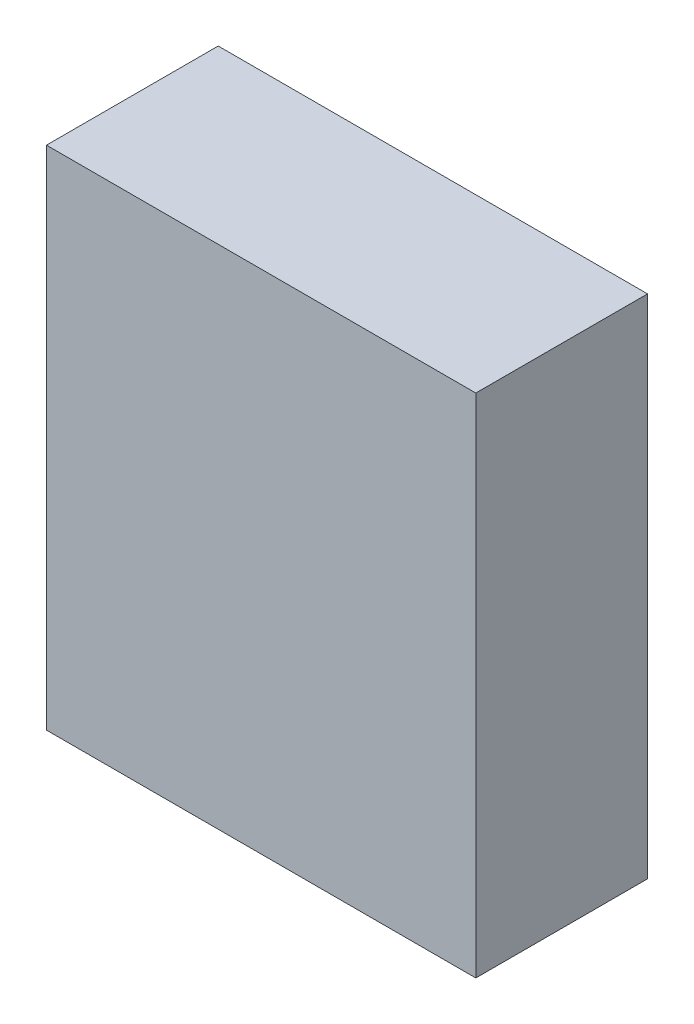
SolidWorks part; units mm, degrees
ref_plane "Спереди" through (0, 0, 0) normal (0, 0, 1) x (1, 0, 0)
ref_plane "Сверху" through (0, 0, 0) normal (0, 1, 0) x (1, 0, 0)
ref_plane "Справа" through (0, 0, 0) normal (1, 0, 0) x (0, 0, -1)
sketch "Эскиз1" plane through (0, 0, 0) normal (0, 0, 1) x (1, 0, 0)
  line L1 (-50, -59) -> (50, -59)
  line L2 (-50, -59) -> (-50, 59)
  line L3 (-50, 59) -> (50, 59)
  line L4 (50, -59) -> (50, 59)
  line L5 (-50, -59) -> (50, 59) construction
  line L6 (-50, 59) -> (50, -59) construction
  point P0 (0, 0)
  dimension "D1" = 118
  dimension "D2" = 100
extrude "Бобышка-Вытянуть1" add sketch "Эскиз1" along normal blind 40
